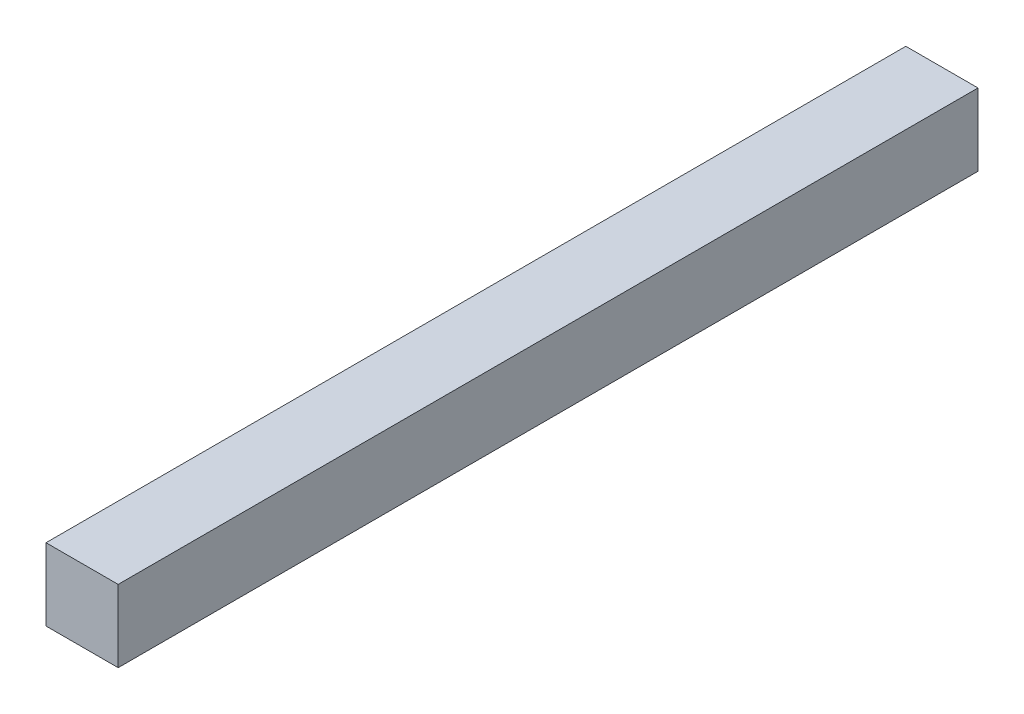
SolidWorks part; units mm, degrees
ref_plane "Front Plane" through (0, 0, 0) normal (0, 0, 1) x (1, 0, 0)
ref_plane "Top Plane" through (0, 0, 0) normal (0, 1, 0) x (1, 0, 0)
ref_plane "Right Plane" through (0, 0, 0) normal (1, 0, 0) x (0, 0, -1)
sketch "Sketch1" plane through (0, 0, 0) normal (0, 0, 1) x (1, 0, 0)
  line L1 (-2.35, -2.35) -> (2.35, -2.35)
  line L2 (-2.35, -2.35) -> (-2.35, 2.35)
  line L3 (-2.35, 2.35) -> (2.35, 2.35)
  line L4 (2.35, -2.35) -> (2.35, 2.35)
  line L5 (-2.35, -2.35) -> (2.35, 2.35) construction
  line L6 (-2.35, 2.35) -> (2.35, -2.35) construction
  point P0 (0, 0)
  dimension "D1" = 4.7
  dimension "D2" = 4.7
extrude "Boss-Extrude1" add sketch "Sketch1" along normal blind 56
